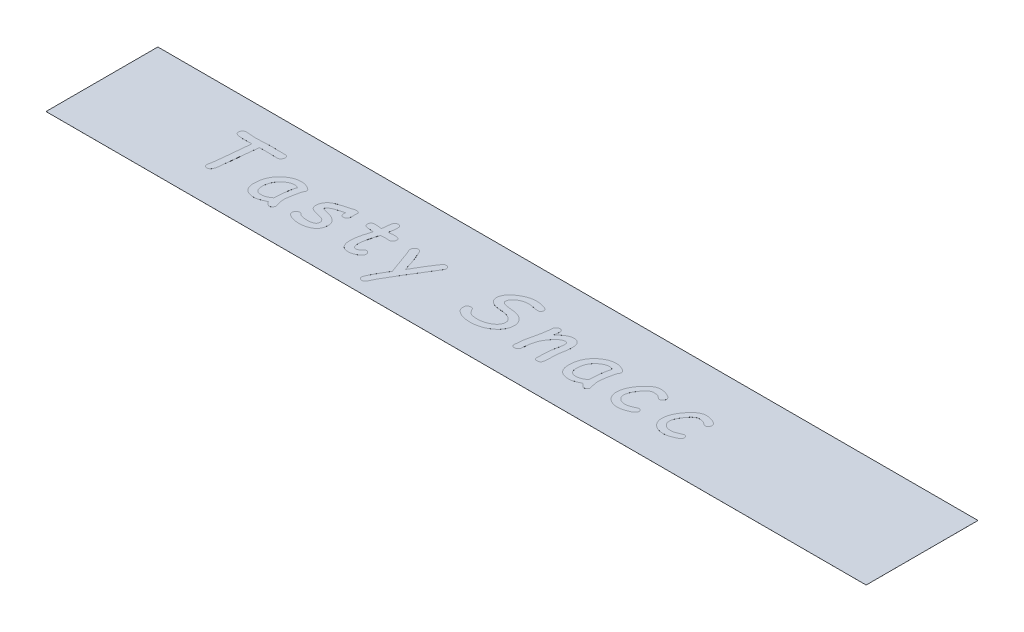
SolidWorks part; units mm, degrees
ref_plane "Front Plane" through (0, 0, 0) normal (0, 0, 1) x (1, 0, 0)
ref_plane "Top Plane" through (0, 0, 0) normal (0, 1, 0) x (1, 0, 0)
ref_plane "Right Plane" through (0, 0, 0) normal (1, 0, 0) x (0, 0, -1)
sketch "Sketch1" plane through (0, 0, 0) normal (0, 1, 0) x (1, 0, 0)
  line L1 (-48.3742, 27.9329) -> (91.3258, 27.9329)
  line L2 (-48.3742, 27.9329) -> (-48.3742, 8.8829)
  line L3 (-48.3742, 8.8829) -> (91.3258, 8.8829)
  line L4 (91.3258, 27.9329) -> (91.3258, 8.8829)
  dimension "D1" = 19.05
  dimension "D2" = 139.7
extrude "Boss-Extrude1" add sketch "Sketch1" along normal blind 0.0025
sketch "Sketch2" plane through (0, 0.0025, 0) normal (0, 1, 0) x (1, 0, 0)
  text T0 "Tasty Snacc" font "Comic Sans MS" height 8.89
extrude "Boss-Extrude2" add sketch "Sketch2" along normal blind 0.0025
